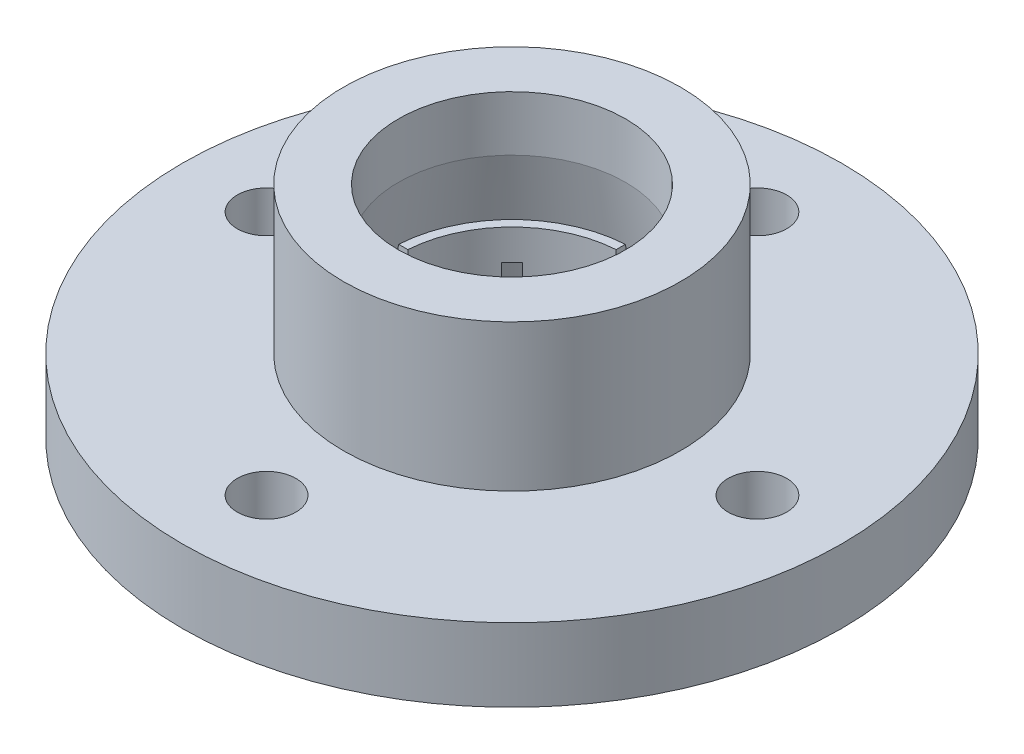
SolidWorks part; units mm, degrees
ref_plane "Front Plane" through (0, 0, 0) normal (0, 0, 1) x (1, 0, 0)
ref_plane "Top Plane" through (0, 0, 0) normal (0, 1, 0) x (1, 0, 0)
ref_plane "Right Plane" through (0, 0, 0) normal (1, 0, 0) x (0, 0, -1)
sketch "Sketch2" plane through (0, 0, 0) normal (1, 0, 0) x (0, 0, -1)
  line L0 (-3.1, 6) -> (-3.1, 4.5)
  line L1 (-3.1, 4.5) -> (-3.8935, 0)
  line L2 (-3.8935, 0) -> (-9, 0)
  line L3 (-9, 0) -> (-9, 2)
  line L4 (-9, 2) -> (-4.6, 2)
  line L5 (-4.6, 2) -> (-4.6, 6)
  line L6 (-4.6, 6) -> (-3.1, 6)
  line L7 (-7, -996.8199) -> (-7, 49003.1801) construction
  line L8 (-4.9, -996.8199) -> (-4.9, 49003.1801) construction
  line L9 (-9.1, -996.8199) -> (-9.1, 49003.1801) construction
  point P14 (-3.1, 4.4041)
  dimension "D1" = 9
  dimension "D2" = 3.1
  dimension "D3" = 6
  dimension "D4" = 2
  dimension "D7" = 7
  dimension "D8" = 1.5
  dimension "D9" = 10
  dimension "D10" = 4.5
  dimension "D5" = 2.1
  dimension "D6" = 2.1
ref_axis "Axis1" through (0, 8.4, 0) along (0, -1, 0)
revolve "Revolve1" add sketch "Sketch2" angle 360 about axis through (0, 8.4, 0) along (0, -1, 0)
sketch "Sketch3" plane through (0, 2, 0) normal (0, 1, 0) x (1, 0, 0)
  circle A1 centre (0, -6.7) radius 2.1 construction
  circle A2 centre (0, 0) radius 4.6 construction
  point P4 (0, 0)
  point P5 (0, 0)
  dimension "D1" = 4.2
hole_wizard "M2x0.4 Tapped Hole1" positions "Sketch4" profile "Sketch5" tap size "M2x0.4" standard "ANSI Metric" end condition through all
sketch "Sketch4" plane through (0, 2, 0) normal (0, 1, 0) x (1, 0, 0)
  point P0 (0, -6.7)
sketch "Sketch5" plane through (0, 2, 6.7) normal (1, 0, 0) x (0, 0, 1)
  line L0 (0, 0) -> (0, 2)
  line L1 (0, 2) -> (0.8, 2)
  line L2 (0.8, 2) -> (0.8, 0)
  line L5 (0.8, 0) -> (0, 0)
  line L11 (0, -6.35) -> (0, 107.95) construction
  dimension "Thru Tap Drill Dia." = 1.6
  dimension "Thru Tap Drill Depth" = 2
cosmetic thread "Hole Thread1" parameters "D2"=2
pattern_circular "CirPattern1" count 4 over 360 about axis through (0, 0, 0) along (0, 1, 0) of "M2x0.4 Tapped Hole1"
cosmetic thread "Hole Thread2" parameters "D2"=2
cosmetic thread "Hole Thread3" parameters "D2"=2
cosmetic thread "Hole Thread4" parameters "D2"=2
sketch "Sketch6" plane through (0, 0, 0) normal (0, 0, 1) x (1, 0, 0)
  line L0 (3.05, 2.8356) -> (3.05, -0.5)
  line L1 (3.05, -0.5) -> (3.8, -0.5)
  line L2 (3.8, -0.5) -> (3.8, 0)
  line L3 (3.8, 0) -> (3.3, 2.8356)
  line L4 (3.3, 2.8356) -> (3.05, 2.8356)
  line L5 (0, 8.4) -> (0, -0.4) construction
  line L6 (-3.8935, 0) -> (3.8935, 0) construction
  point P7 (3.7734, -0.283)
  point P10 (3.05, 2.5471)
  point P11 (3.813, 0)
  dimension "D1" = 3.05
  dimension "D2" = 10
  dimension "D3" = 0.5
  dimension "D4" = 3.8
  dimension "D5" = 0.25
revolve "Revolve2" add sketch "Sketch6" angle 360 about axis through (0, 8.4, 0) along (0, -1, 0)
sketch "Sketch7" plane through (0, 2.8356, 0) normal (0, 1, 0) x (1, 0, 0)
  line L0 (0, 0) -> (0, 6)
  dimension "D1" = 6
extrude "Cut-Extrude-Thin1" cut sketch "Sketch7" against normal blind 2.5 thin thin type mid plane wall 0.4
sketch "Sketch8" plane through (0, -0.5, 0) normal (0, -1, 0) x (1, 0, 0)
  line L0 (0, 0) -> (4.2426, 4.2426)
  line L1 (0, -1000) -> (0, 49000) construction
  dimension "D1" = 45
  dimension "D2" = 6
extrude "Cut-Extrude-Thin2" cut sketch "Sketch8" against normal blind 2.5 thin thin type mid plane wall 0.4
pattern_circular "CirPattern2" count 4 over 360 about axis through (0, 0, 0) along (0, 1, 0) of "Cut-Extrude-Thin1", "Cut-Extrude-Thin2"
